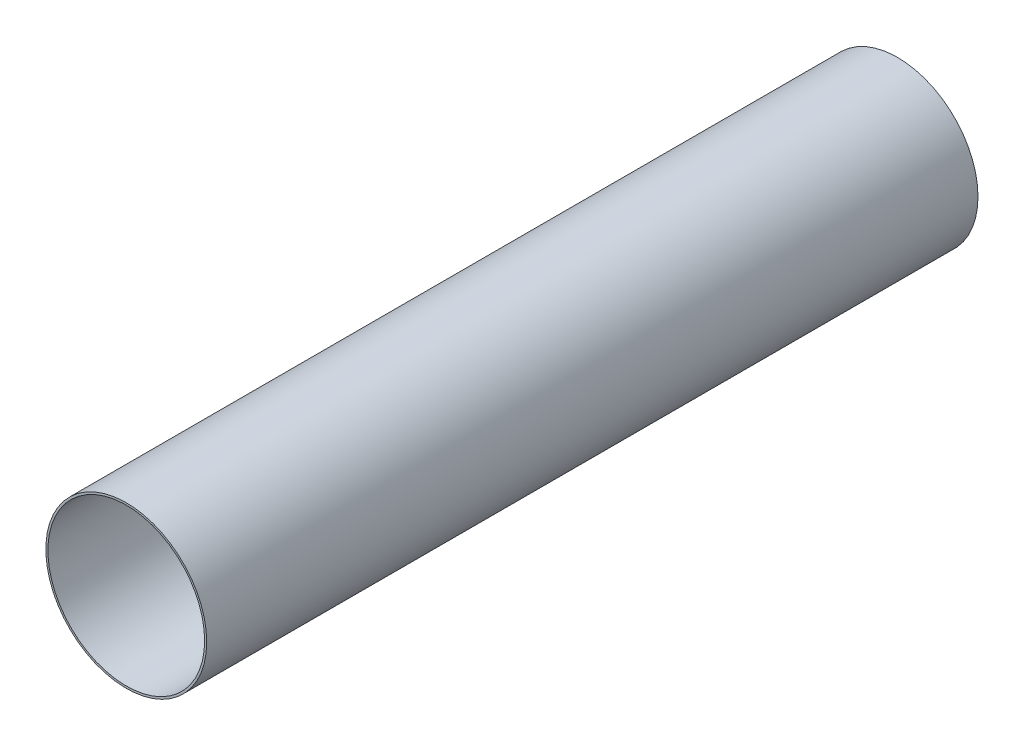
SolidWorks part; units mm, degrees
material "E-Glass Fiber"
ref_plane "Front" through (0, 0, 0) normal (0, 0, 1) x (1, 0, 0)
ref_plane "Top" through (0, 0, 0) normal (0, 1, 0) x (1, 0, 0)
ref_plane "Right" through (0, 0, 0) normal (1, 0, 0) x (0, 0, -1)
sketch "Sketch1" plane through (0, 0, 0) normal (0, 0, 1) x (1, 0, 0)
  circle A0 centre (0, 0) radius 78.2
  circle A1 centre (0, 0) radius 76.2
  dimension "D1" = 156.4
  dimension "D2" = 152.4
extrude "Boss-Extrude1" add sketch "Sketch1" along normal blind 750
